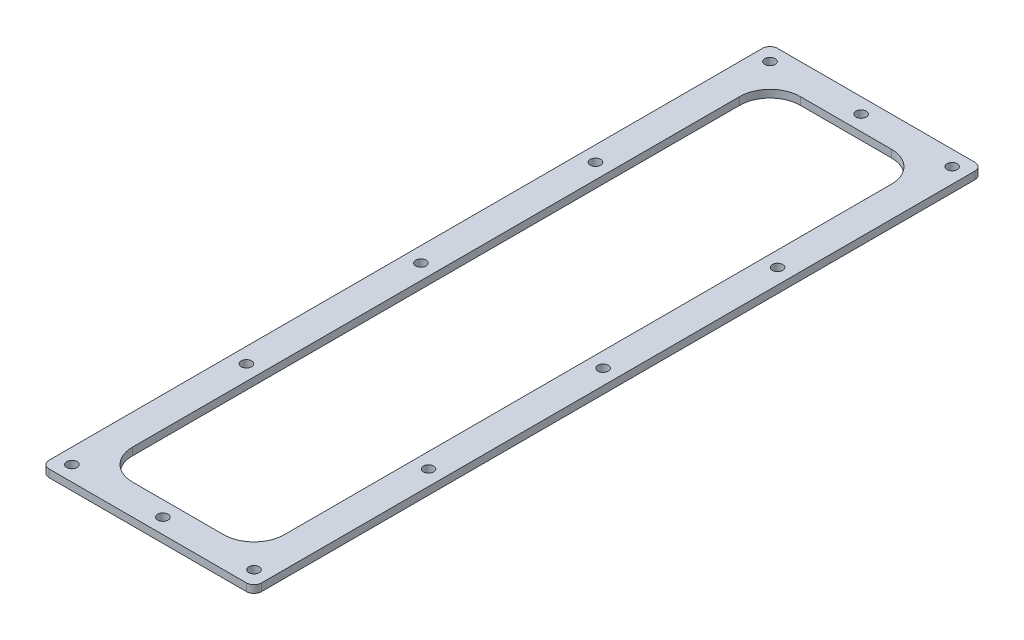
SolidWorks part; units mm, degrees
ref_plane "Front Plane" through (0, 0, 0) normal (0, 0, 1) x (1, 0, 0)
ref_plane "Top Plane" through (0, 0, 0) normal (0, 1, 0) x (1, 0, 0)
ref_plane "Right Plane" through (0, 0, 0) normal (1, 0, 0) x (0, 0, -1)
sketch "Sketch1" plane through (0, 0, 0) normal (0, 1, 0) x (1, 0, 0)
  line L1 (-44.45, 152.4) -> (44.45, 152.4)
  line L2 (-44.45, 152.4) -> (-44.45, -152.4)
  line L3 (-44.45, -152.4) -> (44.45, -152.4)
  line L4 (44.45, 152.4) -> (44.45, -152.4)
  line L14 (0, 0) -> (0, 187.5455) construction
  line L21 (0, 0) -> (44.45, 0) construction
  line L37 (-31.75, 139.7) -> (31.75, 139.7)
  line L40 (-31.75, 139.7) -> (-31.75, -139.7)
  line L43 (-31.75, -139.7) -> (31.75, -139.7)
  line L46 (31.75, 139.7) -> (31.75, -139.7)
  point P4 (0, 152.4)
  point P6 (-44.45, 0)
  point P7 (0, 0)
  point P9 (-44.45, 138.5494)
  point P10 (44.45, 138.5494)
  dimension "D4" = 279.4
  dimension "D2" = 88.9
  dimension "D3" = 304.8
  dimension "D6" = 12.7
  dimension "D12" = 12.7
extrude "Boss-Extrude1" add sketch "Sketch1" along normal blind 3.175
sketch "Sketch7" plane through (0, 3.175, 0) normal (0, 1, 0) x (1, 0, 0)
  line L1 (-44.45, 152.4) -> (-44.45, -152.4) construction
  line L2 (0, 0) -> (0, 246.0772) construction
  line L3 (0, 0) -> (301.4392, 0) construction
  line L4 (44.45, 152.4) -> (-44.45, 152.4) construction
  circle A0 centre (-38.1, 146.05) radius 2.159
  circle A1 centre (-38.1, 73.025) radius 2.159
  circle A2 centre (-38.1, 0) radius 2.159
  circle A3 centre (-38.1, -73.025) radius 2.159
  circle A5 centre (-38.1, -146.05) radius 2.159
  circle A6 centre (38.1, -146.05) radius 2.159
  circle A7 centre (38.1, -73.025) radius 2.159
  circle A8 centre (38.1, 0) radius 2.159
  circle A9 centre (38.1, 73.025) radius 2.159
  circle A10 centre (38.1, 146.05) radius 2.159
  circle A11 centre (0, 146.05) radius 2.159
  circle A12 centre (0, -146.05) radius 2.159
  dimension "D1" = 4.318
  dimension "D2" = 6.35
  dimension "D3" = 6.35
  dimension "D4" = 73.025
  dimension "D5" = 73.025
  dimension "D6" = 73.025
  dimension "D7" = 73.025
  dimension "D8" = 6.35
extrude "Cut-Extrude2" cut sketch "Sketch7" against normal through all
fillet "Fillet1" radius 12.7 4 edges at (31.75, 1.5875, 139.7) (-31.75, 1.5875, 139.7) (-31.75, 1.5875, -139.7) (31.75, 1.5875, -139.7)
sketch "Sketch8" [suppressed] plane through (0, 3.175, 0) normal (0, 1, 0) x (1, 0, 0)
  line L0 (184.15, 139.7) -> (-184.15, 139.7) construction
  line L1 (0, 139.7) -> (0, 110.7046) construction
  circle A0 centre (-15.7442, 133.35) radius 2.159
  circle A1 centre (15.7442, 133.35) radius 2.159
  dimension "D5" = 4.318
  dimension "D6" = 4.318
  dimension "D1" = 6.35
  dimension "D2" = 6.35
  dimension "D3" = 31.4884
  dimension "D4" = 15.7442
fillet "Fillet3" radius 3.175 4 edges at (-44.45, 1.5875, 152.4) (44.45, 1.5875, 152.4) (44.45, 1.5875, -152.4) (-44.45, 1.5875, -152.4)
